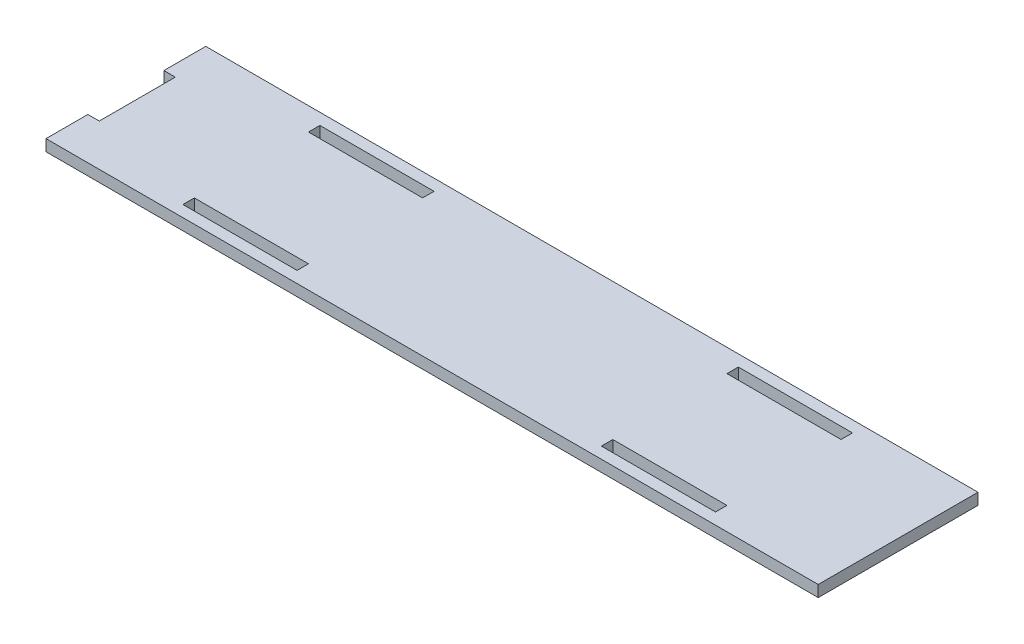
SolidWorks part; units mm, degrees
material "ABS"
ref_plane "Front Plane" through (0, 0, 0) normal (0, 0, 1) x (1, 0, 0)
ref_plane "Top Plane" through (0, 0, 0) normal (0, 1, 0) x (1, 0, 0)
ref_plane "Right Plane" through (0, 0, 0) normal (1, 0, 0) x (0, 0, -1)
sketch "Sketch1" plane through (0, 0, 0) normal (0, 1, 0) x (1, 0, 0)
  line L0 (0, 31) -> (0, 42)
  line L1 (0, 0) -> (203, 0)
  line L2 (0, 0) -> (0, 11)
  line L3 (0, 42) -> (203, 42)
  line L4 (203, 0) -> (203, 42)
  line L5 (0, 31) -> (3, 31)
  line L7 (0, 11) -> (3, 11)
  line L8 (3, 31) -> (3, 11)
  line L9 (33, 6) -> (63, 6)
  line L10 (33, 6) -> (33, 3)
  line L11 (33, 3) -> (63, 3)
  line L12 (63, 6) -> (63, 3)
  line L13 (143, 6) -> (173, 6)
  line L14 (143, 6) -> (143, 3)
  line L15 (143, 3) -> (173, 3)
  line L16 (173, 6) -> (173, 3)
  line L21 (3, 21) -> (139.3519, 21) construction
  line L22 (173, 36) -> (173, 39)
  line L23 (143, 39) -> (173, 39)
  line L24 (143, 36) -> (143, 39)
  line L25 (143, 36) -> (173, 36)
  line L26 (63, 36) -> (63, 39)
  line L27 (33, 39) -> (63, 39)
  line L28 (33, 36) -> (33, 39)
  line L29 (33, 36) -> (63, 36)
  point P21 (63, 4.5)
  dimension "D1" = 203
  dimension "D2" = 42
  dimension "D3" = 20
  dimension "D4" = 3
  dimension "D5" = 11
  dimension "D6" = 30
  dimension "D7" = 3
  dimension "D8" = 3
  dimension "D9" = 33
  dimension "D10" = 30
  dimension "D11" = 3
  dimension "D12" = 3
  dimension "D13" = 80
extrude "Boss-Extrude1" add sketch "Sketch1" along normal blind 3
